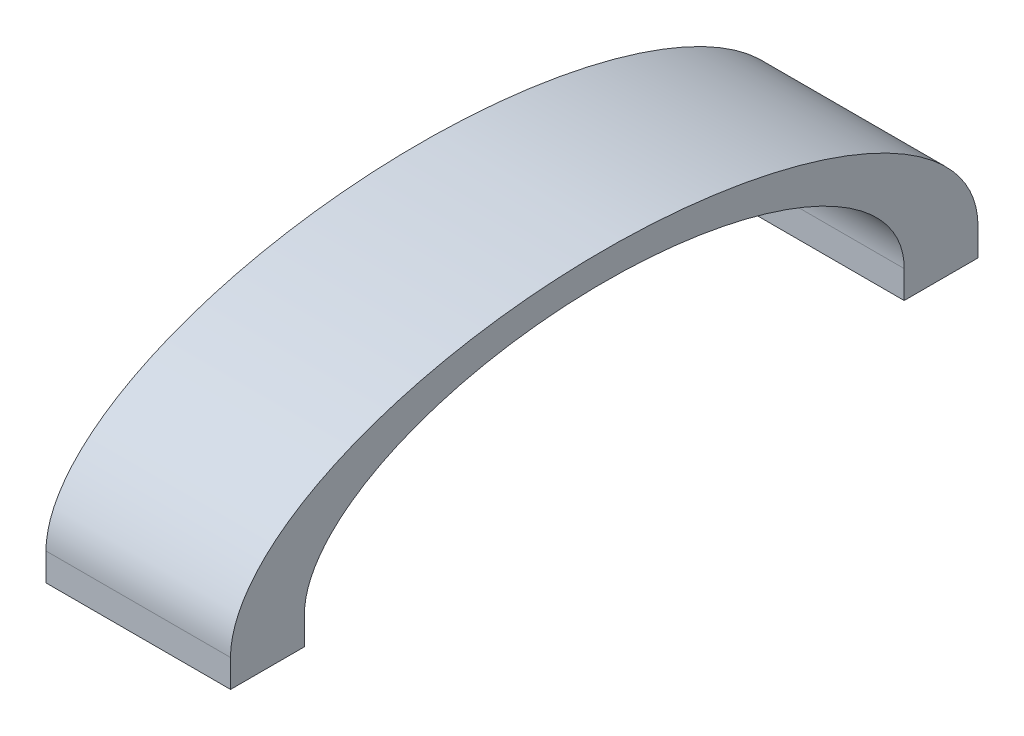
SolidWorks part; units mm, degrees
ref_plane "Front Plane" through (0, 0, 0) normal (0, 0, 1) x (1, 0, 0)
ref_plane "Top Plane" through (0, 0, 0) normal (0, 1, 0) x (1, 0, 0)
ref_plane "Right Plane" through (0, 0, 0) normal (1, 0, 0) x (0, 0, -1)
sketch "Sketch2" plane through (0, 0, 0) normal (1, 0, 0) x (0, 0, -1)
  line L3 (32.5, 0) -> (40.5, 0)
  line L4 (0, 15) -> (0, 0) construction
  line L5 (0, 15) -> (0, 18)
  ellipse E0 centre (0, 0) end of major axis (-32.5, 0) minor radius 15 (0, 15) -> (32.5, 0) cw
  ellipse E1 centre (0, 0) end of major axis (40.5, 0) minor radius 18 (0, 18) -> (40.5, 0) cw
  point P7 (36.5, 0)
  dimension "D2" = 73
  dimension "D3" = 15
  dimension "D1" = 3
  dimension "D4" = 8
extrude "Main" add sketch "Sketch2" along normal mid plane 20
sketch "Sketch4" plane through (0, 0, 0) normal (0, -1, 0) x (1, 0, 0)
  line L4 (-10, -32.5) -> (-10, -40.5)
  line L5 (-10, -40.5) -> (10, -40.5)
  line L6 (10, -40.5) -> (10, -32.5)
  line L7 (10, -32.5) -> (-10, -32.5)
  line L8 (-10, -32.5) -> (-10, -40.5)
  line L9 (-10, -40.5) -> (10, -40.5)
  line L10 (10, -40.5) -> (10, -32.5)
  line L11 (10, -32.5) -> (-10, -32.5)
  dimension "D1" = 0
extrude "Insert extension" add sketch "Sketch4" along normal blind 3
sketch "Sketch5" plane through (0, -3, 0) normal (0, -1, 0) x (1, 0, 0)
  line L0 (-10, -36.5) -> (10, -36.5) construction
  line L1 (-10, -32.5) -> (-10, -40.5) construction
  line L2 (10, -40.5) -> (10, -32.5) construction
  circle A0 centre (0, -36.5) radius 2.1
  dimension "D1" = 4.2
extrude "Insert hole" cut sketch "Sketch5" against normal blind 5.7
mirror "Mirror1" about plane through (10, 15, 0) normal (0, 0, -1) of "Insert hole", "Insert extension", "Main"
